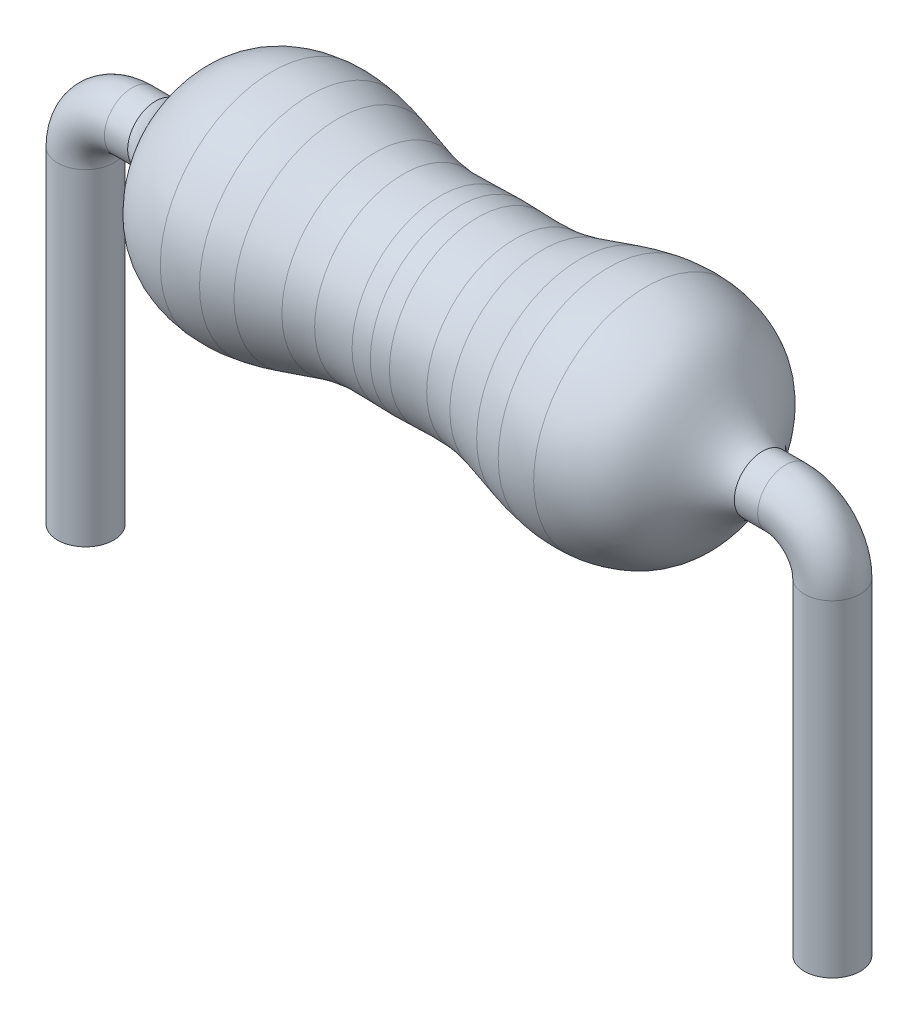
SolidWorks part; units mm, degrees
ref_plane "Front Plane" through (0, 0, 0) normal (0, 0, 1) x (1, 0, 0)
ref_plane "Top Plane" through (0, 0, 0) normal (0, 1, 0) x (1, 0, 0)
ref_plane "Right Plane" through (0, 0, 0) normal (1, 0, 0) x (0, 0, -1)
sketch "Эскиз3" plane through (0, 0, 0) normal (0, 0, 1) x (1, 0, 0)
  line L0 (0, 0) -> (0, 0.95) construction
  line L1 (0, 0) -> (-3.25, 0)
  line L2 (-3.25, 0.3) -> (-3.25, 0)
  line L3 (3.25, 0.3) -> (3.25, 0)
  line L4 (0, 0) -> (3.25, 0)
  spline S7 degree 3 poles (-2, 1.2) (-2.236, 1.1816) (-2.7893, 1.0051) (-2.9711, 0.4301) (-3.25, 0.3) knots 0.780397 0.780397 0.780397 0.780397 0.876745 1 1 1 1
  spline S8 degree 3 poles (-1.6, 1.18) (-1.7314, 1.2017) (-1.8646, 1.2105) (-2, 1.2) knots 0.725131 0.725131 0.725131 0.725131 0.780397 0.780397 0.780397 0.780397
  spline S9 degree 3 poles (-1.3, 1.1111) (-1.3498, 1.125) (-1.4493, 1.1514) (-1.5497, 1.1718) (-1.6, 1.18) knots 0.682659 0.682659 0.682659 0.682659 0.703993 0.725131 0.725131 0.725131 0.725131
  spline S10 degree 3 poles (-0.9, 0.9977) (-1.0336, 1.0307) (-1.1663, 1.0735) (-1.3, 1.1111) knots 0.625412 0.625412 0.625412 0.625412 0.682659 0.682659 0.682659 0.682659
  spline S11 degree 3 poles (-0.6, 0.9462) (-0.6167, 0.9476) (-0.7176, 0.9571) (-0.8172, 0.9772) (-0.9, 0.9977) knots 0.58292 0.58292 0.58292 0.58292 0.589942 0.625412 0.625412 0.625412 0.625412
  spline S12 degree 3 poles (-0.2, 0.9457) (-0.3344, 0.9411) (-0.4682, 0.9358) (-0.6, 0.9462) knots 0.527476 0.527476 0.527476 0.527476 0.58292 0.58292 0.58292 0.58292
  spline S13 degree 3 poles (0, 0.95) (-0.0667, 0.9501) (-0.1334, 0.948) (-0.2, 0.9457) knots 0.500017 0.500017 0.500017 0.500017 0.527476 0.527476 0.527476 0.527476
  spline S14 degree 3 poles (0, 0.95) (0.0667, 0.9501) (0.1334, 0.948) (0.2, 0.9457) knots 0.500017 0.500017 0.500017 0.500017 0.527476 0.527476 0.527476 0.527476
  spline S15 degree 3 poles (0.2, 0.9457) (0.3344, 0.9411) (0.4682, 0.9358) (0.6, 0.9462) knots 0.527476 0.527476 0.527476 0.527476 0.58292 0.58292 0.58292 0.58292
  spline S16 degree 3 poles (0.6, 0.9462) (0.6167, 0.9476) (0.7176, 0.9571) (0.8172, 0.9772) (0.9, 0.9977) knots 0.58292 0.58292 0.58292 0.58292 0.589942 0.625412 0.625412 0.625412 0.625412
  spline S17 degree 3 poles (0.9, 0.9977) (1.0336, 1.0307) (1.1663, 1.0735) (1.3, 1.1111) knots 0.625412 0.625412 0.625412 0.625412 0.682659 0.682659 0.682659 0.682659
  spline S18 degree 3 poles (1.3, 1.1111) (1.3498, 1.125) (1.4493, 1.1514) (1.5497, 1.1718) (1.6, 1.18) knots 0.682659 0.682659 0.682659 0.682659 0.703993 0.725131 0.725131 0.725131 0.725131
  spline S19 degree 3 poles (1.6, 1.18) (1.7314, 1.2017) (1.8646, 1.2105) (2, 1.2) knots 0.725131 0.725131 0.725131 0.725131 0.780397 0.780397 0.780397 0.780397
  spline S20 degree 3 poles (2, 1.2) (2.236, 1.1816) (2.7893, 1.0051) (2.9711, 0.4301) (3.25, 0.3) knots 0.780397 0.780397 0.780397 0.780397 0.876745 1 1 1 1
sketch "Эскиз4" plane through (0, 0, 0) normal (0, 0, 1) x (1, 0, 0)
  line L0 (2.9873, 0) -> (3.5, 0)
  line L1 (4, -0.5) -> (4, -4)
  arc A0 (4, -0.5) -> (3.5, 0) centre (3.5, -0.5) ccw
  dimension "D2" = 0.5
  dimension "D1" = 4
  dimension "D3" = 4
ref_plane "Плоскость1" through (0, -4, 0) normal (0, 1, 0) x (1, 0, 0)
sketch "Эскиз5" plane through (0, -4, 0) normal (0, 1, 0) x (1, 0, 0)
  circle A0 centre (4, 0) radius 0.3
  dimension "D1" = 0.6
revolve "Повернуть2" add sketch "Эскиз3" angle 360 about L4
sweep "По траектории2" add profiles "Эскиз5" path "Эскиз4"
mirror "Зеркальное отражение1" about plane through (0, 0, 0) normal (1, 0, 0) of "По траектории2"
